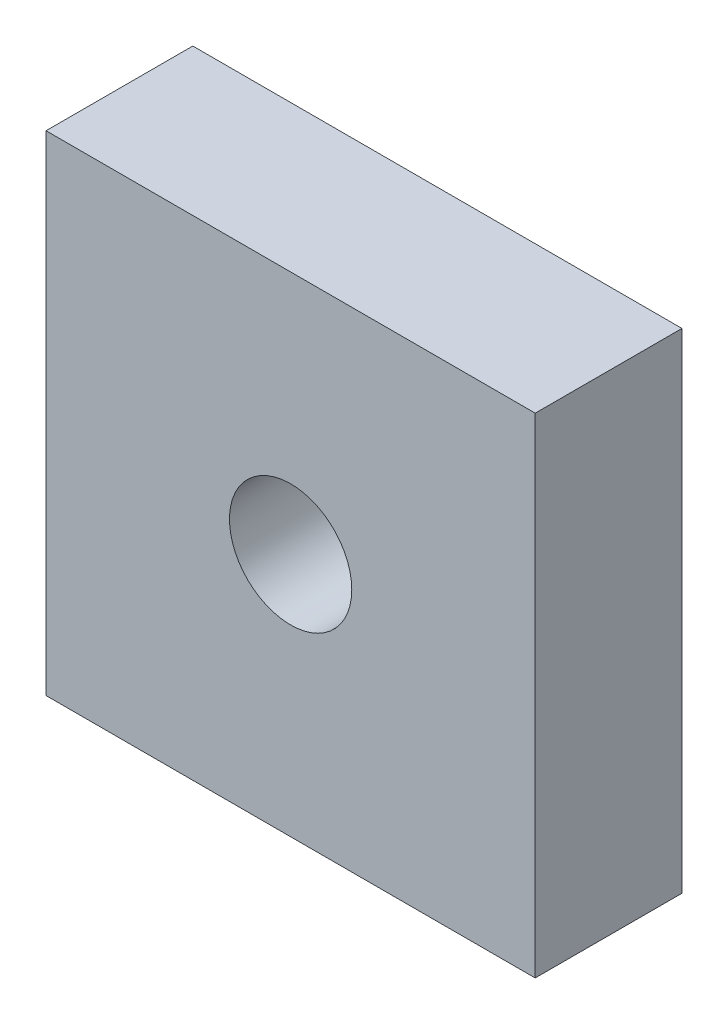
SolidWorks part; units mm, degrees
ref_plane "Plano frontal" through (0, 0, 0) normal (0, 0, 1) x (1, 0, 0)
ref_plane "Plano superior" through (0, 0, 0) normal (0, 1, 0) x (1, 0, 0)
ref_plane "Plano direito" through (0, 0, 0) normal (1, 0, 0) x (0, 0, -1)
sketch "Esboço1" plane through (0, 0, 0) normal (0, 0, 1) x (1, 0, 0)
  line L1 (-10, 10) -> (10, 10)
  line L2 (-10, 10) -> (-10, -10)
  line L3 (-10, -10) -> (10, -10)
  line L4 (10, 10) -> (10, -10)
  line L5 (-10, 10) -> (10, -10) construction
  line L6 (-10, -10) -> (10, 10) construction
  circle A0 centre (0, 0) radius 2.5
  point P0 (0, 0)
  dimension "D2" = 5
  dimension "D1" = 20
extrude "Ressalto-extrusão1" add sketch "Esboço1" along normal blind 6
